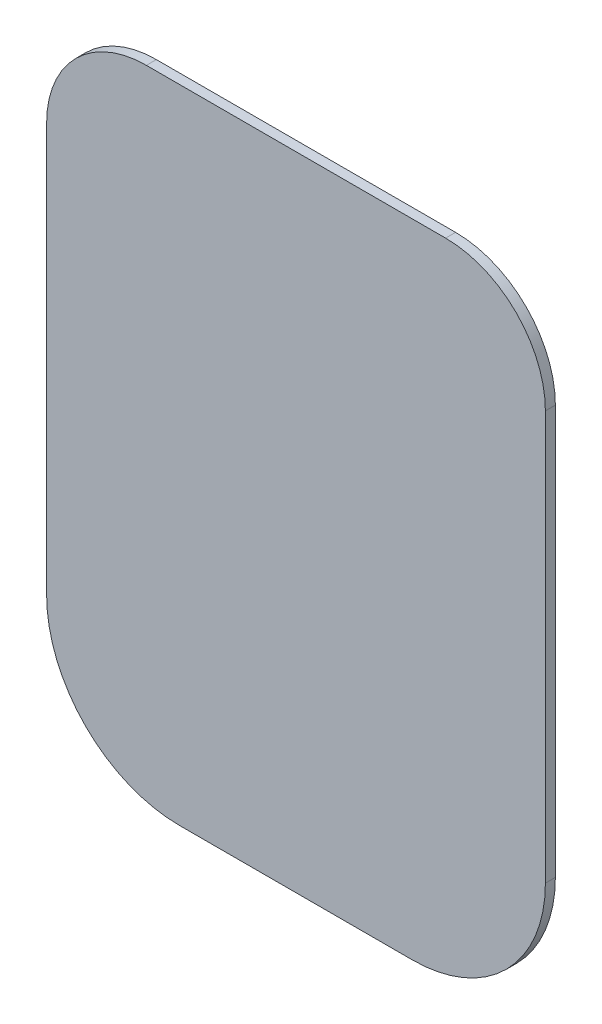
SolidWorks part; units mm, degrees
ref_plane "Front Plane" through (0, 0, 0) normal (0, 0, 1) x (1, 0, 0)
ref_plane "Top Plane" through (0, 0, 0) normal (0, 1, 0) x (1, 0, 0)
ref_plane "Right Plane" through (0, 0, 0) normal (1, 0, 0) x (0, 0, -1)
sketch "Sketch1" plane through (0, 0, 0) normal (0, 0, 1) x (1, 0, 0)
  line L0 (0, 96.5) -> (0, -96.5) construction
  line L1 (-75, 96.5) -> (75, 96.5) construction
  line L2 (-75, 96.5) -> (-75, -96.5) construction
  line L3 (-75, -96.5) -> (75, -96.5) construction
  line L4 (75, 96.5) -> (75, -96.5) construction
  line L5 (-45, 96.5) -> (45, 96.5)
  line L6 (-35, -96.5) -> (35, -96.5) construction
  line L7 (-75, 66.5) -> (75, 66.5) construction
  line L8 (-75, 66.5) -> (-75, -56.5)
  line L9 (-75, -56.5) -> (75, -56.5) construction
  line L10 (75, 66.5) -> (75, -56.5)
  line L11 (-0.5, -96.5) -> (0.5, -96.5) construction
  line L12 (-35, -96.5) -> (-0.5, -96.5)
  line L13 (0.5, -96.5) -> (35, -96.5)
  line L14 (-0.5, -96.5) -> (0.5, -96.5)
  arc A0 (-75, 66.5) -> (-45, 96.5) centre (-45, 66.5) cw
  arc A1 (45, 96.5) -> (75, 66.5) centre (45, 66.5) cw
  arc A2 (-75, -56.5) -> (-35, -96.5) centre (-35, -56.5) ccw
  arc A3 (35, -96.5) -> (75, -56.5) centre (35, -56.5) ccw
  point P6 (0, 0)
  point P10 (0, 96.5)
  point P19 (0, -96.5)
  point P23 (0, -96.5)
  dimension "D3" = 40
  dimension "D4" = 30
  dimension "D1" = 193
  dimension "D2" = 150
  dimension "D5" = 1
  dimension "D6" = 96.5
extrude "Boss-Extrude1" add sketch "Sketch1" along normal blind 3
